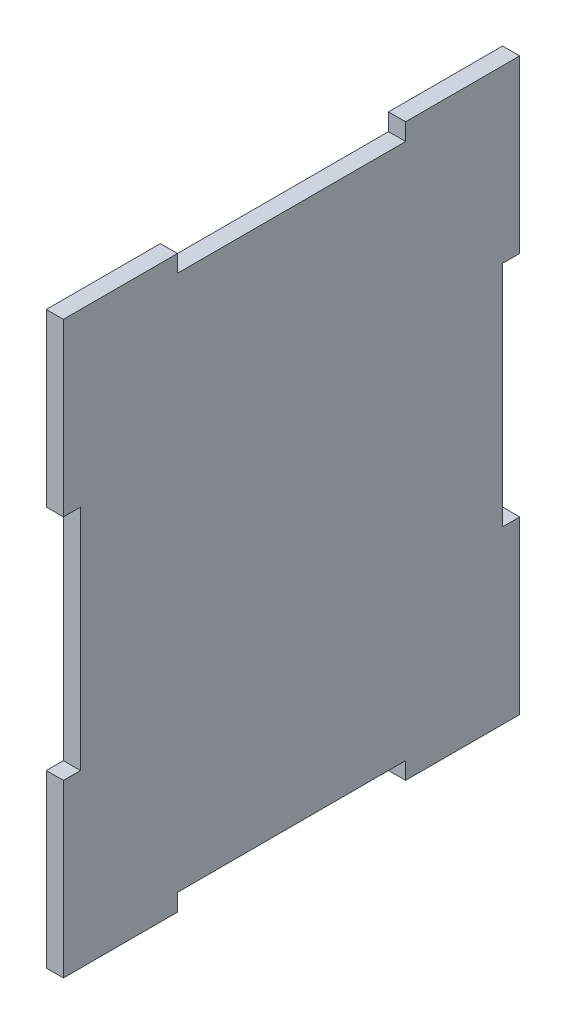
SolidWorks part; units mm, degrees
ref_plane "Plan de face" through (0, 0, 0) normal (0, 0, 1) x (1, 0, 0)
ref_plane "Plan de dessus" through (0, 0, 0) normal (0, 1, 0) x (1, 0, 0)
ref_plane "Plan de droite" through (0, 0, 0) normal (1, 0, 0) x (0, 0, -1)
sketch "Esquisse1" plane through (0, 0, 0) normal (1, 0, 0) x (0, 0, -1)
  line L0 (34.2645, 38.0749) -> (54.2645, 38.0749)
  line L1 (-25.7355, 38.0749) -> (-5.7355, 38.0749)
  line L2 (-25.7355, 38.0749) -> (-25.7355, 8.0749)
  line L3 (-25.7355, -61.9251) -> (-5.7355, -61.9251)
  line L4 (54.2645, 38.0749) -> (54.2645, 8.0749)
  line L5 (34.2645, -61.9251) -> (54.2645, -61.9251)
  line L6 (-22.7355, 8.0749) -> (-22.7355, -31.9251)
  line L7 (51.2645, 8.0749) -> (54.2645, 8.0749)
  line L9 (54.2645, -31.9251) -> (51.2645, -31.9251)
  line L10 (54.2645, -31.9251) -> (54.2645, -61.9251)
  line L12 (51.2645, 8.0749) -> (51.2645, -31.9251)
  line L13 (-25.7355, -31.9251) -> (-22.7355, -31.9251)
  line L14 (-25.7355, -31.9251) -> (-25.7355, -61.9251)
  line L19 (-22.7355, 8.0749) -> (-25.7355, 8.0749)
  line L22 (-5.7355, -61.9251) -> (-5.7355, -58.9251)
  line L23 (-5.7355, -58.9251) -> (34.2645, -58.9251)
  line L24 (34.2645, -61.9251) -> (34.2645, -58.9251)
  line L26 (-5.7355, 38.0749) -> (-5.7355, 35.0749)
  line L27 (-5.7355, 35.0749) -> (34.2645, 35.0749)
  line L28 (34.2645, 38.0749) -> (34.2645, 35.0749)
  dimension "D1" = 100
  dimension "D2" = 80
  dimension "D3" = 3
  dimension "D4" = 30
  dimension "D5" = 40
  dimension "D6" = 20
  dimension "D7" = 30
extrude "Boss.-Extru.2" add sketch "Esquisse1" along normal blind 3
